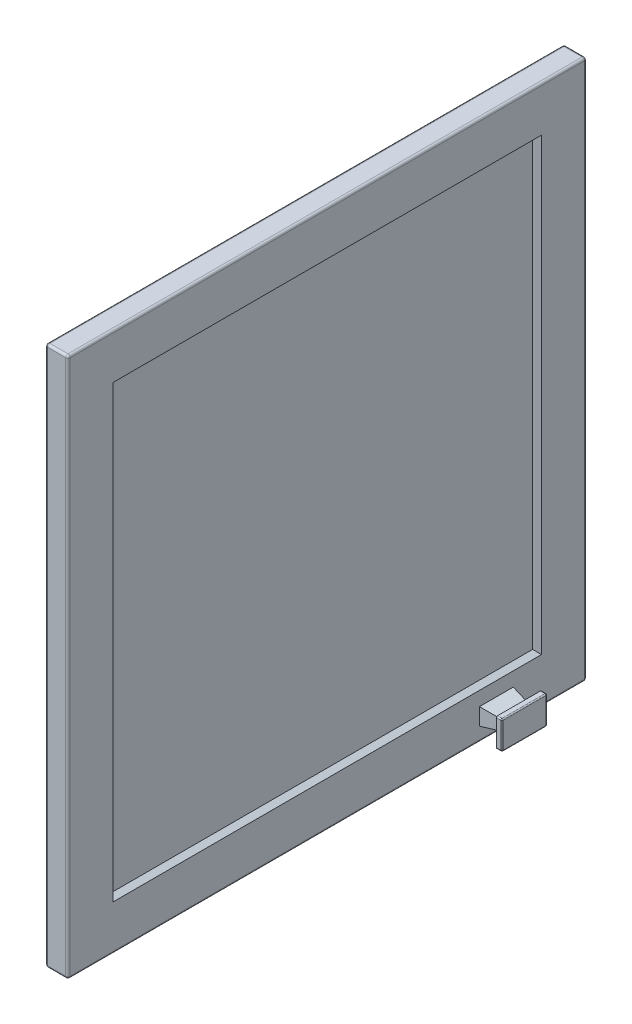
SolidWorks part; units mm, degrees
ref_plane "Front Plane" through (0, 0, 0) normal (1, 0, 0) x (0, 1, 0)
ref_plane "Top Plane" through (0, 0, 0) normal (0, 0, 1) x (0, 1, 0)
ref_plane "Right Plane" through (0, 0, 0) normal (0, 1, 0) x (-1, 0, 0)
sketch "Sketch1" plane through (0, 0, 0) normal (1, 0, 0) x (0, 1, 0)
  line L1 (0, 0) -> (479, 0)
  line L2 (0, 0) -> (0, 460)
  line L3 (0, 460) -> (479, 460)
  line L4 (479, 0) -> (479, 460)
  dimension "D1" = 460
  dimension "D2" = 479
extrude "Boss-Extrude1" add sketch "Sketch1" along normal mid plane 20
sketch "Sketch2" plane through (10, 0, 0) normal (1, 0, 0) x (0, 1, 0)
  line L8 (40, 420) -> (40, 40)
  line L9 (40, 40) -> (439, 40)
  line L10 (439, 40) -> (439, 420)
  line L11 (439, 420) -> (40, 420)
  line L12 (40, 420) -> (40, 40)
  line L13 (40, 40) -> (439, 40)
  line L14 (439, 40) -> (439, 420)
  line L15 (439, 420) -> (40, 420)
  dimension "D1" = 40
extrude "Cut-Extrude1" cut sketch "Sketch2" against normal blind 5 draft 30
mirror "Mirror1" about plane through (0, 0, 0) normal (1, 0, 0) of "Cut-Extrude1"
sketch "Sketch3" plane through (10, 0, 0) normal (1, 0, 0) x (0, 1, 0)
  line L0 (0, 0) -> (479, 0) construction
  line L1 (446.5, 100) -> (471.5, 100) construction
  line L2 (446.5, 100) -> (446.5, 60) construction
  line L3 (446.5, 60) -> (471.5, 60) construction
  line L4 (471.5, 100) -> (471.5, 60) construction
  line L5 (446.5, 100) -> (471.5, 60) construction
  line L6 (446.5, 60) -> (471.5, 100) construction
  line L8 (479, 0) -> (479, 460) construction
  line L10 (451.5, 65) -> (466.5, 65)
  line L11 (451.5, 65) -> (451.5, 95)
  line L12 (451.5, 95) -> (466.5, 95)
  line L13 (466.5, 65) -> (466.5, 95)
  line L14 (451.5, 65) -> (466.5, 95) construction
  line L15 (451.5, 95) -> (466.5, 65) construction
  point P0 (459, 80)
  point P5 (459, 80)
  dimension "D1" = 25
  dimension "D2" = 40
  dimension "D3" = 80
  dimension "D4" = 20
  dimension "D5" = 5
  dimension "D6" = 10
extrude "Boss-Extrude2" add sketch "Sketch3" along normal blind 20 draft 10
sketch "Sketch4" plane through (30, 0, 0) normal (1, 0, 0) x (0, 1, 0)
  line L0 (446.5, 60) -> (471.5, 60) construction
  line L1 (471.5, 100) -> (471.5, 60) construction
  line L2 (446.5, 100) -> (446.5, 60) construction
  line L3 (446.5, 100) -> (471.5, 100) construction
  line L4 (446.5, 60) -> (471.5, 60)
  line L5 (471.5, 100) -> (471.5, 60)
  line L6 (446.5, 100) -> (446.5, 60)
  line L7 (446.5, 100) -> (471.5, 100)
extrude "Boss-Extrude3" add sketch "Sketch4" along normal blind 5
fillet "Fillet3" radius 2 12 edges at (10, 479, 230) (-10, 479, 230) (10, 239.5, 0) (0, 479, 0) (-10, 239.5, 0) (10, 0, 230) (0, 0, 0) (-10, 0, 230) (0, 479, 460) (10, 239.5, 460) (0, 0, 460) (-10, 239.5, 460)
fillet "Fillet4" radius 1 8 edges at (35, 459, 100) (35, 471.5, 80) (35, 459, 60) (35, 446.5, 80) (32.5, 446.5, 100) (32.5, 446.5, 60) (32.5, 471.5, 60) (32.5, 471.5, 100)
mirror "Mirror2" about plane through (0, 0, 0) normal (0, 1, 0) of bodies 105
delete or keep bodies "Body-Delete/Keep 1" type delete bodies bodies 105
